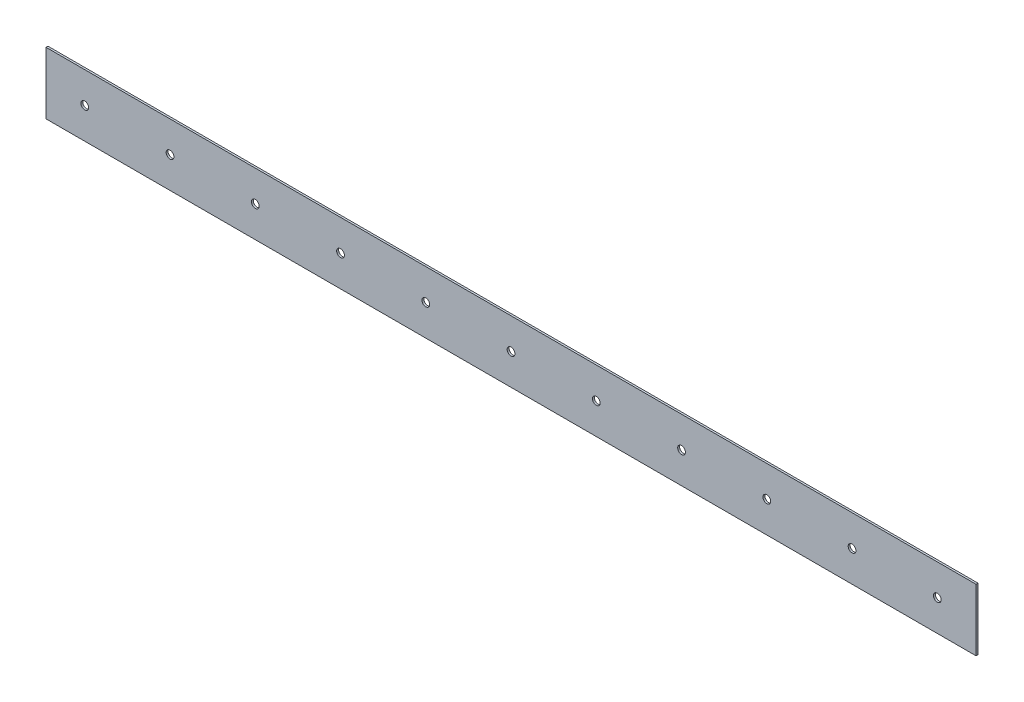
SolidWorks part; units mm, degrees
material "Malleable Cast Iron"
ref_plane "Front" through (0, 0, 0) normal (0, 0, 1) x (1, 0, 0)
ref_plane "Top" through (0, 0, 0) normal (0, 1, 0) x (1, 0, 0)
ref_plane "Right" through (0, 0, 0) normal (1, 0, 0) x (0, 0, -1)
sketch "Sketch1" plane through (0, 0, 0) normal (0, 0, 1) x (1, 0, 0)
  line L5 (-1524, 101.6) -> (1524, 101.6)
  line L6 (-1524, 101.6) -> (-1524, -101.6)
  line L7 (-1524, -101.6) -> (1524, -101.6)
  line L8 (1524, 101.6) -> (1524, -101.6)
  line L9 (-1524, 101.6) -> (1524, -101.6) construction
  line L10 (-1524, -101.6) -> (1524, 101.6) construction
  circle A20 centre (-1397, 0) radius 12.7
  circle A21 centre (-1117.6, 0) radius 12.7
  circle A22 centre (-838.2, 0) radius 12.7
  circle A23 centre (-558.8, 0) radius 12.7
  circle A24 centre (-279.4, 0) radius 12.7
  circle A25 centre (0, 0) radius 12.7
  circle A26 centre (279.4, 0) radius 12.7
  circle A27 centre (558.8, 0) radius 12.7
  circle A28 centre (838.2, 0) radius 12.7
  circle A29 centre (1117.6, 0) radius 12.7
  circle A30 centre (1397, 0) radius 12.7
  point P0 (0, 0)
  point P8 (0, 0)
  point P9 (0, 0)
  dimension "D3" = 25.4
  dimension "D1" = 3048
  dimension "D2" = 203.2
  dimension "D4" = 127
  dimension "D6" = 279.4
  dimension "D5" = 101.6
extrude "Boss-Extrude1" add sketch "Sketch1" along normal blind 6.35
